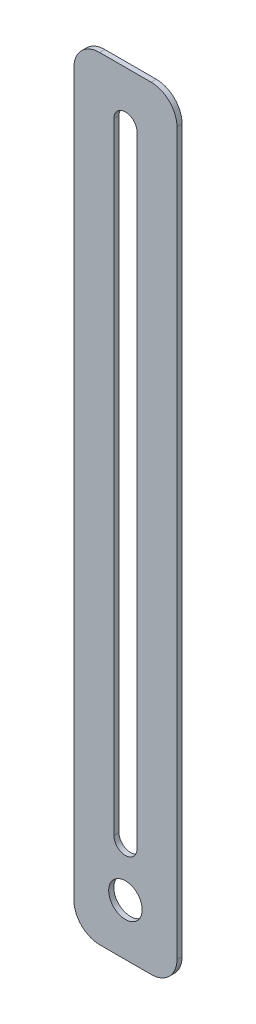
SolidWorks part; units mm, degrees
material "Galvanized Steel"
ref_plane "Front Plane" through (0, 0, 0) normal (0, 0, 1) x (1, 0, 0)
ref_plane "Top Plane" through (0, 0, 0) normal (0, 1, 0) x (1, 0, 0)
ref_plane "Right Plane" through (0, 0, 0) normal (1, 0, 0) x (0, 0, -1)
sketch "Sketch1" plane through (0, 0, 0) normal (0, 0, 1) x (1, 0, 0)
  line L0 (0, -110.5) -> (0, 130.5) construction
  line L1 (-10, -150) -> (10, -150)
  line L2 (-20, -140) -> (-20, 140)
  line L3 (-10, 150) -> (10, 150)
  line L4 (20, -140) -> (20, 140)
  line L5 (-20, -150) -> (20, 150) construction
  line L6 (-20, 150) -> (20, -150) construction
  line L7 (-4.5, -110.5) -> (-4.5, 130.5)
  line L8 (4.5, -110.5) -> (4.5, 130.5)
  circle A0 centre (0, -130) radius 6.5
  arc A1 (-4.5, -110.5) -> (4.5, -110.5) centre (0, -110.5) ccw
  arc A2 (4.5, 130.5) -> (-4.5, 130.5) centre (0, 130.5) ccw
  arc A3 (-10, -150) -> (-20, -140) centre (-10, -140) cw
  arc A4 (10, -150) -> (20, -140) centre (10, -140) ccw
  arc A5 (-20, 140) -> (-10, 150) centre (-10, 140) cw
  arc A6 (10, 150) -> (20, 140) centre (10, 140) cw
  point P0 (0, 0)
  point P10 (0, 10)
  dimension "D3" = 13
  dimension "D4" = 20
  dimension "D5" = 160
  dimension "D6" = 10
  dimension "D1" = 40
  dimension "D2" = 300
extrude "Boss-Extrude1" add sketch "Sketch1" along normal blind 2
